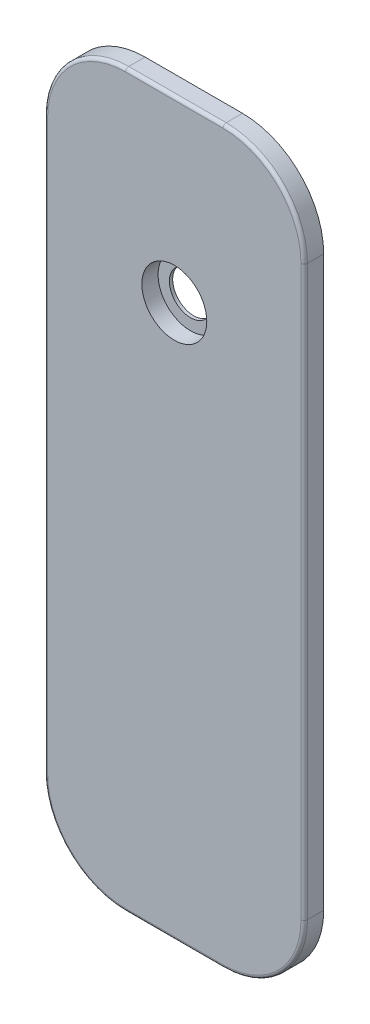
SolidWorks part; units mm, degrees
ref_plane "前视基准面" through (0, 0, 0) normal (0, 0, 1) x (1, 0, 0)
ref_plane "上视基准面" through (0, 0, 0) normal (0, 1, 0) x (1, 0, 0)
ref_plane "右视基准面" through (0, 0, 0) normal (1, 0, 0) x (0, 0, -1)
sketch "草图1" plane through (0, 0, 0) normal (0, 0, 1) x (1, 0, 0)
  line L0 (0, 112.5) -> (0, 0) construction
  line L1 (15, 112.5) -> (-15, 112.5)
  line L2 (40, 87.5) -> (40, -87.5)
  line L3 (15, -112.5) -> (-15, -112.5)
  line L4 (-40, 87.5) -> (-40, -87.5)
  arc A0 (-15, -112.5) -> (-40, -87.5) centre (-15, -87.5) cw
  arc A1 (40, -87.5) -> (15, -112.5) centre (15, -87.5) cw
  arc A2 (15, 112.5) -> (40, 87.5) centre (15, 87.5) cw
  arc A3 (-15, 112.5) -> (-40, 87.5) centre (-15, 87.5) ccw
  circle A4 centre (0, 57.5) radius 6.5
  point P4 (0, 112.5)
  point P6 (-40, 0)
  point P9 (-40, -112.5)
  point P14 (40, 112.5)
  point P17 (-40, 112.5)
  dimension "D3" = 25
  dimension "D4" = 13
  dimension "D1" = 80
  dimension "D2" = 225
  dimension "D5" = 55
extrude "凸台-拉伸1" add sketch "草图1" along normal blind 6
fillet "圆角1" radius 1 8 edges at (32.6777, -105.1777, 6) (0, -112.5, 6) (-32.6777, -105.1777, 6) (-40, 0, 6) (-32.6777, 105.1777, 6) (0, 112.5, 6) (32.6777, 105.1777, 6) (40, 0, 6)
sketch "草图2" plane through (0, 0, 6) normal (0, 0, 1) x (1, 0, 0)
  circle A0 centre (0, 57.5) radius 10
  dimension "D1" = 20
extrude "切除-拉伸1" cut sketch "草图2" against normal blind 5
sketch "草图3" plane through (0, 0, 6) normal (0, 0, 1) x (1, 0, 0)
  line L0 (0, 57.5) -> (0, -119.3917) construction
  line L1 (-39, -47.5) -> (40, -47.5)
  line L2 (-15, 112.5) -> (15, 112.5) construction
  line L3 (40, 87.5) -> (40, -87.5) construction
  line L4 (-39, 87.5) -> (-39, -87.5) construction
  point P8 (40, -47.5)
  point P11 (-39, -47.5)
  dimension "D1" = 160
